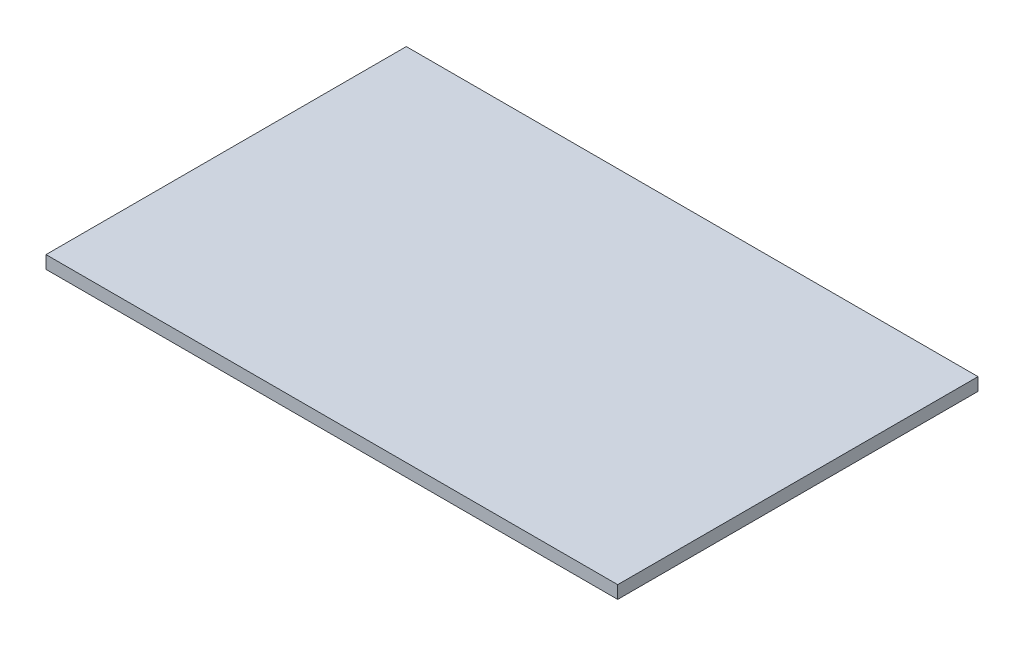
SolidWorks part; units mm, degrees
ref_plane "Ebene vorne" through (0, 0, 0) normal (0, 0, 1) x (1, 0, 0)
ref_plane "Ebene oben" through (0, 0, 0) normal (0, 1, 0) x (1, 0, 0)
ref_plane "Ebene rechts" through (0, 0, 0) normal (1, 0, 0) x (0, 0, -1)
sketch "Skizze1" plane through (0, 0, 0) normal (0, 1, 0) x (1, 0, 0)
  line L1 (-178.5, -112.5) -> (178.5, -112.5)
  line L2 (-178.5, -112.5) -> (-178.5, 112.5)
  line L3 (-178.5, 112.5) -> (178.5, 112.5)
  line L4 (178.5, -112.5) -> (178.5, 112.5)
  line L5 (-178.5, -112.5) -> (178.5, 112.5) construction
  line L6 (-178.5, 112.5) -> (178.5, -112.5) construction
  point P0 (0, 0)
  dimension "D1" = 357
  dimension "D2" = 225
extrude "Aufsatz-Linear austragen1" add sketch "Skizze1" along normal blind 8
